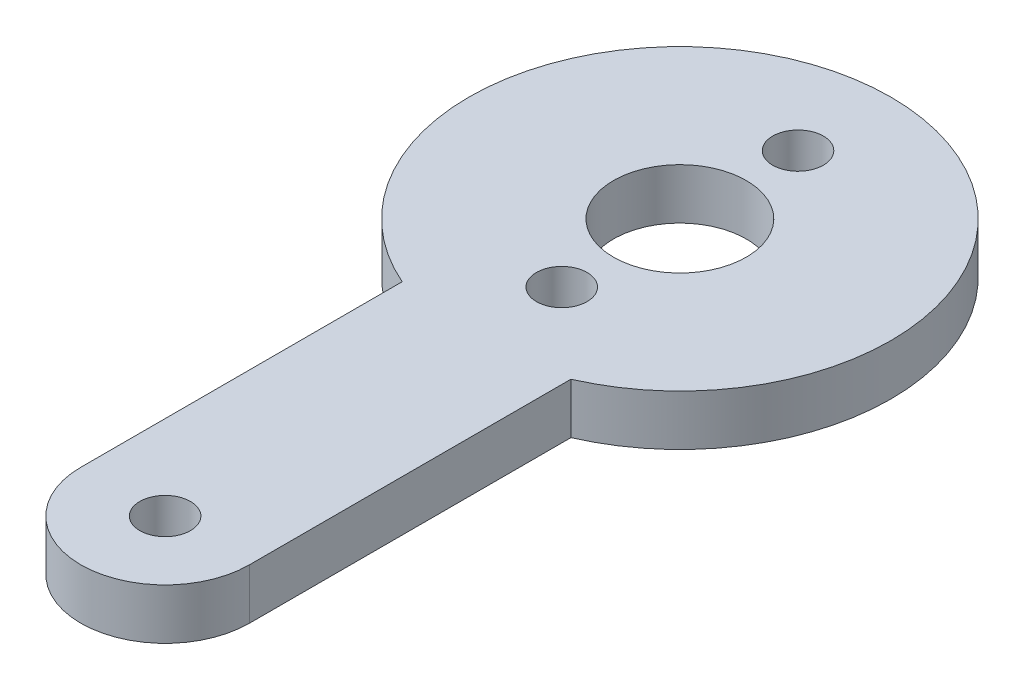
SolidWorks part; units mm, degrees
ref_plane "Front Plane" through (0, 0, 0) normal (0, 0, 1) x (1, 0, 0)
ref_plane "Top Plane" through (0, 0, 0) normal (0, 1, 0) x (1, 0, 0)
ref_plane "Right Plane" through (0, 0, 0) normal (1, 0, 0) x (0, 0, -1)
sketch "Sketch1" plane through (0, 0, 0) normal (0, 1, 0) x (1, 0, 0)
  line L0 (0, 0) -> (0, -30.5) construction
  line L1 (5, 0) -> (5, -30.5) construction
  line L2 (-5, 0) -> (-5, -30.5) construction
  line L3 (-5, -11.4564) -> (-5, -30.5)
  line L4 (-5, -30.5) -> (5, -30.5) construction
  line L5 (5, -30.5) -> (5, -11.4564)
  line L6 (0, 0) -> (0, 7) construction
  arc A0 (5, 0) -> (-5, 0) centre (0, 0) ccw construction
  arc A1 (-5, -30.5) -> (5, -30.5) centre (0, -30.5) ccw construction
  circle A2 centre (0, 0) radius 12.5 construction
  arc A3 (-5, -11.4564) -> (5, -11.4564) centre (0, 0) cw
  arc A4 (-5, -30.5) -> (5, -30.5) centre (0, -30.5) ccw
  circle A5 centre (0, 0) radius 3.935
  circle A6 centre (0, 7) radius 1.5
  circle A7 centre (0, -7) radius 1.5
  circle A8 centre (0, -30.5) radius 1.5
  point P3 (0, -15.25)
  dimension "D1" = 5
  dimension "D2" = 25
  dimension "D4" = 7
  dimension "D6" = 3
  dimension "D7" = 3
  dimension "D3" = 30.5
  dimension "D5" = 7
extrude "Boss-Extrude1" add sketch "Sketch1" along normal blind 3 contours L3 A4 L5 A3 A7 A6 A5
